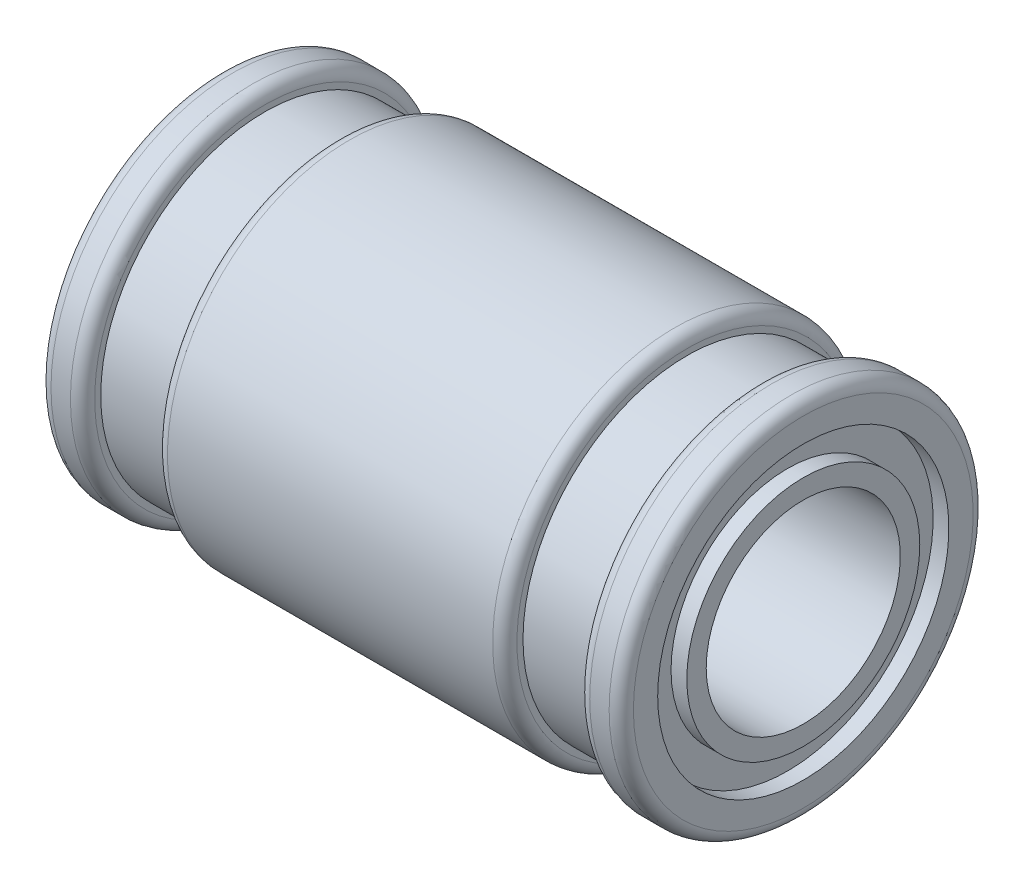
SolidWorks part; units mm, degrees
ref_plane "Front Plane" through (0, 0, 0) normal (0, 0, 1) x (1, 0, 0)
ref_plane "Top Plane" through (0, 0, 0) normal (0, 1, 0) x (1, 0, 0)
ref_plane "Right Plane" through (0, 0, 0) normal (1, 0, 0) x (0, 0, -1)
sketch "Sketch1" plane through (0, 0, 0) normal (0, 0, 1) x (1, 0, 0)
  line L0 (0, 0) -> (30264.8712, 0) construction
  line L2 (0, 4) -> (24, 4)
  line L3 (0, 4) -> (0, 7.5)
  line L4 (0, 7.5) -> (24, 7.5)
  line L5 (24, 4) -> (24, 7.5)
  line L6 (1.8, 7.5) -> (4.8, 7.5)
  line L7 (1.8, 7.5) -> (1.8, 6.75)
  line L8 (1.8, 6.75) -> (4.8, 6.75)
  line L9 (4.8, 7.5) -> (4.8, 6.75)
  line L10 (19.2, 7.5) -> (22.2, 7.5)
  line L11 (19.2, 7.5) -> (19.2, 6.75)
  line L12 (19.2, 6.75) -> (22.2, 6.75)
  line L13 (22.2, 7.5) -> (22.2, 6.75)
  line L14 (0, 6) -> (0.65, 6)
  line L15 (0, 6) -> (0, 4.8)
  line L16 (0, 4.8) -> (0.65, 4.8)
  line L17 (0.65, 6) -> (0.65, 4.8)
  line L18 (24, 6) -> (23.35, 6)
  line L19 (24, 6) -> (24, 4.8)
  line L20 (24, 4.8) -> (23.35, 4.8)
  line L21 (23.35, 6) -> (23.35, 4.8)
  point P19 (23.35, 5.4)
  point P20 (0, 0)
  dimension "D1" = 4
  dimension "D2" = 7.5
  dimension "D3" = 24
  dimension "D4" = 3
  dimension "D5" = 0.75
  dimension "D6" = 1.2
  dimension "D7" = 0.65
  dimension "D8" = 1.5
  dimension "D9" = 3
  dimension "D10" = 0.75
  dimension "D11" = 1.8
  dimension "D12" = 1.8
  dimension "D13" = 1.2
  dimension "D14" = 0.65
revolve "Revolve1" add sketch "Sketch1" angle 360 about L0
fillet "Fillet4" radius 0.5 1 edges at (0, 0, 7.5)
fillet "Fillet5" radius 0.5 5 edges at (1.8, 0, 7.5) (19.2, 0, 7.5) (22.2, 0, 7.5) (24, 0, 7.5) (4.8, 0, 7.5)
